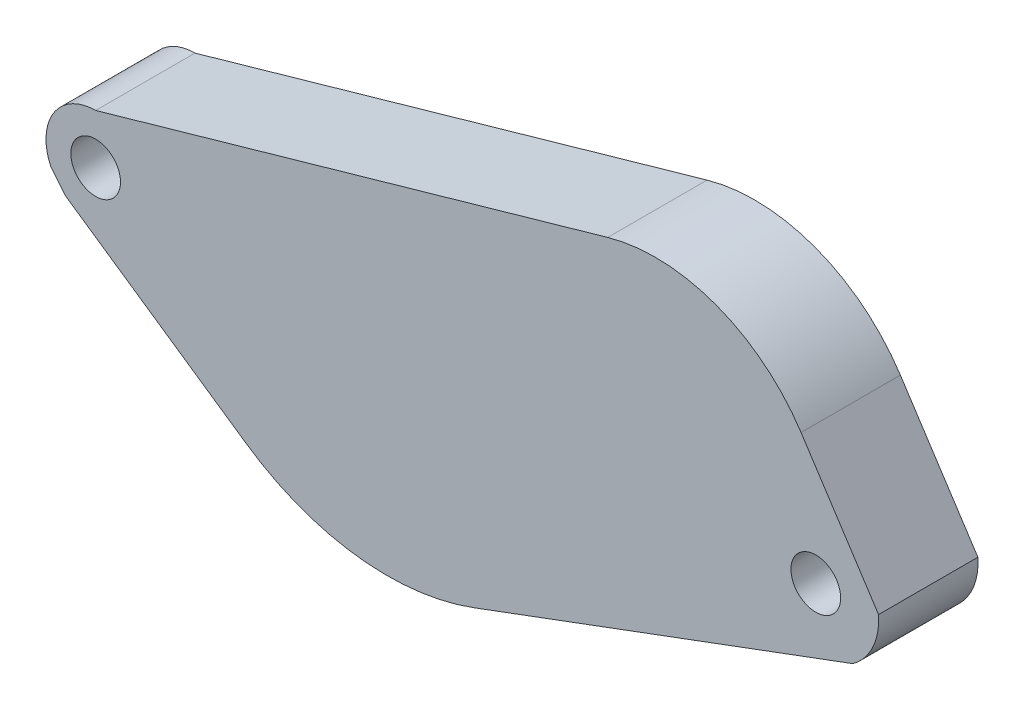
SolidWorks part; units mm, degrees
ref_plane "Front Plane" through (0, 0, 0) normal (0, 0, 1) x (1, 0, 0)
ref_plane "Top Plane" through (0, 0, 0) normal (0, 1, 0) x (1, 0, 0)
ref_plane "Right Plane" through (0, 0, 0) normal (1, 0, 0) x (0, 0, -1)
sketch "Sketch1" plane through (0, 0, 0) normal (0, 0, 1) x (1, 0, 0)
  line L0 (-13.0251, 0) -> (-12.0251, 0) construction
  line L1 (-14.2573, -1.5751) -> (-14.8289, -0.8638)
  line L2 (-6.9399, -6.5991) -> (-14.2573, -1.5751)
  line L5 (15.3821, 4.9723) -> (18.5032, 0.1822)
  line L6 (2.2086, -7.7269) -> (17.4718, -2.0457)
  line L7 (-13.0251, 2) -> (7.5971, 7.8824)
  line L9 (14.9749, 0) -> (15.9749, 0) construction
  arc A0 (2.2086, -7.7269) -> (-6.9399, -6.5991) centre (-1.2798, 1.6449) cw
  arc A1 (-13.0251, 2) -> (-14.8289, -0.8638) centre (-13.0251, 0) ccw
  circle A2 centre (15.9749, 0) radius 1
  circle A3 centre (-13.0251, 0) radius 1
  arc A4 (17.4718, -2.0457) -> (18.5032, 0.1822) centre (15.9749, 0) ccw
  arc A5 (7.5971, 7.8824) -> (15.3821, 4.9723) centre (9.5172, 1.1509) cw
  point P3 (1.4749, 0)
  dimension "D2" = 7
  dimension "D1" = 10
extrude "Boss-Extrude1" add sketch "Sketch1" along normal blind 4
